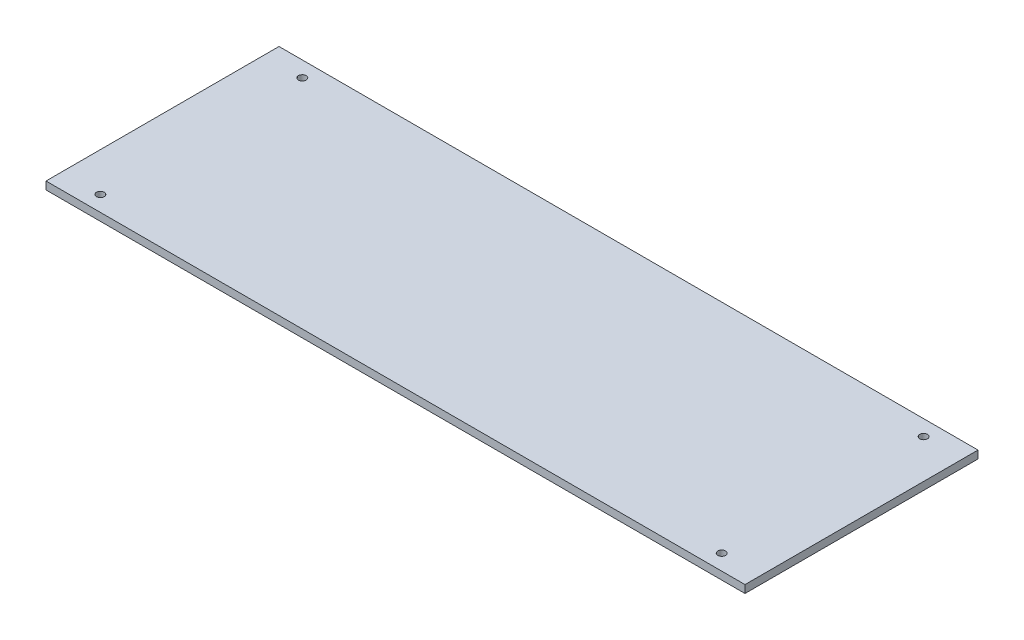
SolidWorks part; units mm, degrees
ref_plane "Front Plane" through (0, 0, 0) normal (0, 0, 1) x (1, 0, 0)
ref_plane "Top Plane" through (0, 0, 0) normal (0, 1, 0) x (1, 0, 0)
ref_plane "Right Plane" through (0, 0, 0) normal (1, 0, 0) x (0, 0, -1)
sketch "Sketch1" plane through (0, 0, 0) normal (0, 1, 0) x (1, 0, 0)
  line L1 (-225, 75) -> (225, 75)
  line L2 (-225, 75) -> (-225, -75)
  line L3 (-225, -75) -> (225, -75)
  line L4 (225, 75) -> (225, -75)
  line L5 (-225, 75) -> (225, -75) construction
  line L6 (-225, -75) -> (225, 75) construction
  point P0 (0, 0)
  dimension "D1" = 150
  dimension "D2" = 450
extrude "Boss-Extrude1" add sketch "Sketch1" along normal blind 5
sketch "Sketch2" plane through (0, 5, 0) normal (0, 1, 0) x (1, 0, 0)
  line L1 (-200, 65) -> (200, 65) construction
  line L2 (-200, 65) -> (-200, -65) construction
  line L3 (-200, -65) -> (200, -65) construction
  line L4 (200, 65) -> (200, -65) construction
  line L5 (-200, 65) -> (200, -65) construction
  line L6 (-200, -65) -> (200, 65) construction
  circle A0 centre (-200, 65) radius 2.5
  circle A1 centre (-200, -65) radius 2.5
  circle A2 centre (200, 65) radius 2.5
  circle A3 centre (200, -65) radius 2.5
  point P0 (0, 0)
  dimension "D3" = 5
  dimension "D1" = 130
  dimension "D2" = 400
extrude "Cut-Extrude1" cut sketch "Sketch2" against normal through all
